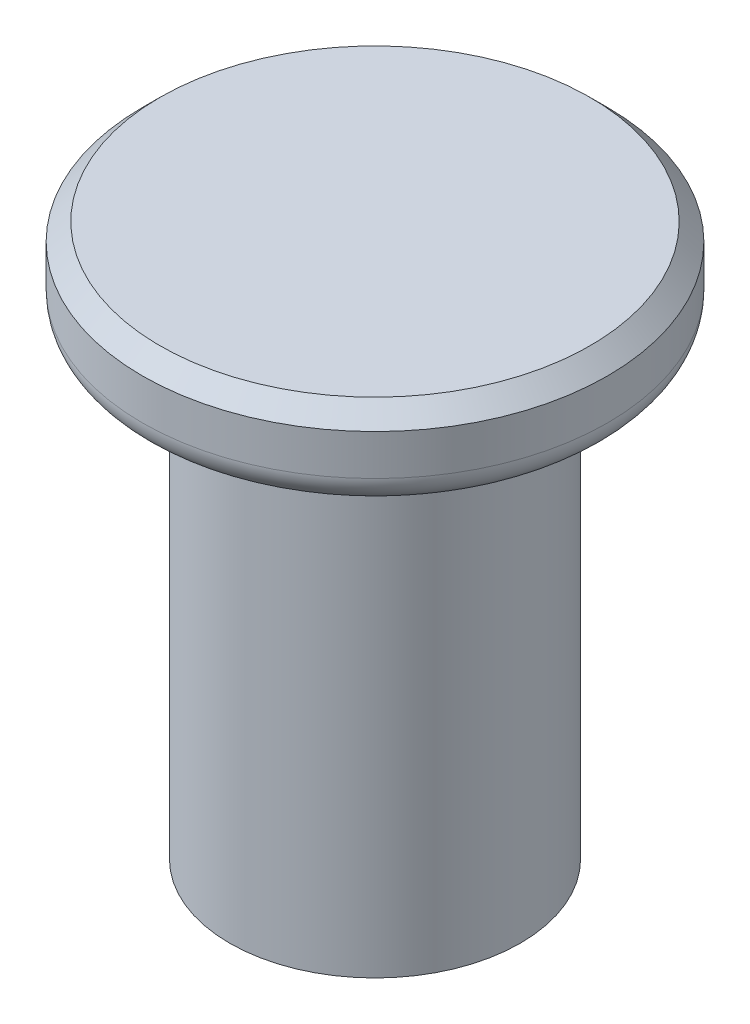
SolidWorks part; units mm, degrees
ref_plane "前视基准面" through (0, 0, 0) normal (0, 0, 1) x (1, 0, 0)
ref_plane "上视基准面" through (0, 0, 0) normal (0, 1, 0) x (1, 0, 0)
ref_plane "右视基准面" through (0, 0, 0) normal (1, 0, 0) x (0, 0, -1)
sketch "草图1" plane through (0, 0, 0) normal (0, 0, 1) x (1, 0, 0)
  line L0 (0, -1000) -> (0, 49000) construction
sketch "草图2" plane through (0, 0, 0) normal (0, 0, 1) x (1, 0, 0)
  line L0 (0, -23.2628) -> (4, -23.2628)
  line L1 (0, -201000) -> (0, 249000) construction
  line L2 (4, -23.2628) -> (4, -24.7628)
  line L3 (4, -24.7628) -> (2.5, -24.7628)
  line L4 (2.5, -24.7628) -> (2.5, -32.7628)
  line L5 (2.5, -32.7628) -> (0, -32.7628)
  line L6 (0, -32.7628) -> (0, -23.2628)
revolve "旋转1" add sketch "草图2" angle 360 about L0
chamfer "倒角1" distance 0.3 angle 45 1 edges at (4, -23.2628, 0)
fillet "圆角1" radius 0.5 1 edges at (4, -24.7628, 0)
